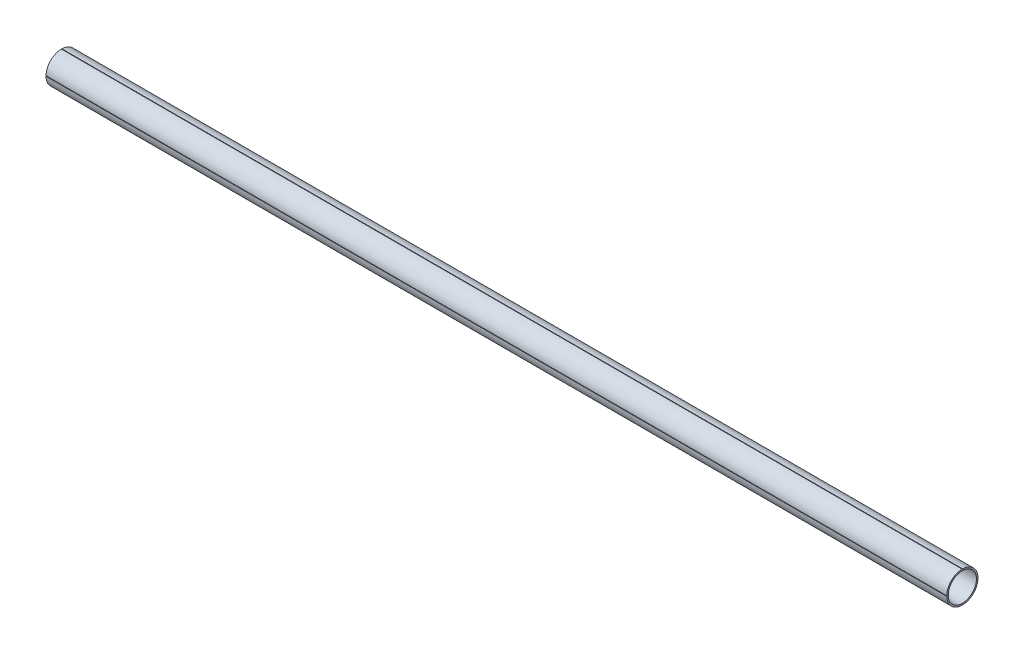
SolidWorks part; units mm, degrees
material "6061-T6 (SS)"
ref_plane "Front Plane" through (0, 0, 0) normal (0, 0, 1) x (1, 0, 0)
ref_plane "Top Plane" through (0, 0, 0) normal (0, 1, 0) x (1, 0, 0)
ref_plane "Right Plane" through (0, 0, 0) normal (1, 0, 0) x (0, 0, -1)
ref_plane "End Plane" through (457.2, 0, 0) normal (1, 0, 0) x (0, 0, -1)
sketch "Sketch1" plane through (457.2, 0, 0) normal (1, 0, 0) x (0, 0, -1)
  line L0 (-0.25, -15.873) -> (0, -15.575)
  line L1 (0, -15.575) -> (0.25, -15.873)
  line L2 (15.873, -0.25) -> (15.575, 0)
  line L3 (15.575, 0) -> (15.873, 0.25)
  line L4 (0.25, 15.873) -> (0, 15.575)
  line L5 (0, 15.575) -> (-0.25, 15.873)
  line L6 (-15.873, 0.25) -> (-15.575, 0)
  line L7 (-15.575, 0) -> (-15.873, -0.25)
  arc A0 (0.25, -15.873) -> (15.873, -0.25) centre (0, 0) ccw
  arc A1 (15.873, 0.25) -> (0.25, 15.873) centre (0, 0) ccw
  arc A2 (-0.25, 15.873) -> (-15.873, 0.25) centre (0, 0) ccw
  arc A3 (-15.873, -0.25) -> (-0.25, -15.873) centre (0, 0) ccw
  circle A4 centre (0, 0) radius 14.3
  circle A5 centre (0, 0) radius 15.575 construction
  dimension "D1" = 28.6
  dimension "D2" = 15.875
extrude "Boss-Extrude1" add sketch "Sketch1" against normal blind 914.4
ref_plane "Plane2" [suppressed] through (253.365, 0, 0) normal (-1, 0, 0) x (0, 0, 1)
other "SurfaceCut1" [suppressed]
ref_plane "Plane3" [suppressed] through (-253.365, 0, 0) normal (1, 0, 0) x (0, 0, -1)
other "SurfaceCut2" [suppressed]
equation "\"L\" = 36"
equation "\"D1@End Plane\"= \"L\" / 2"
equation "\"D1@Boss-Extrude1\"= \"L\""
